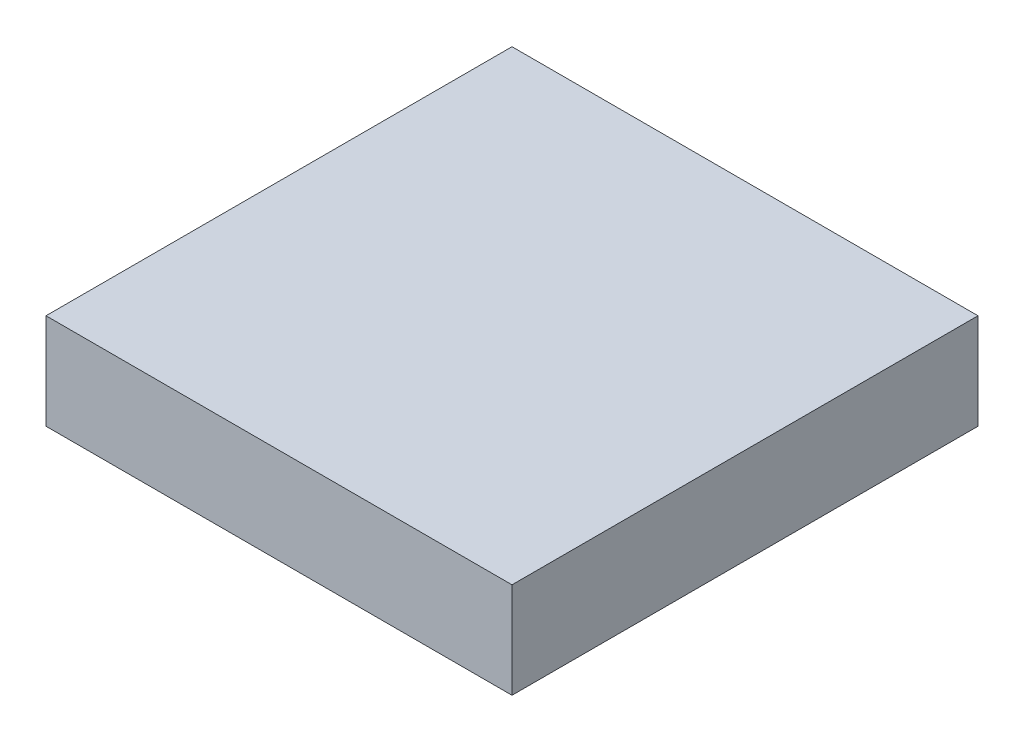
SolidWorks part; units mm, degrees
material "Pine"
ref_plane "Front Plane" through (0, 0, 0) normal (0, 0, 1) x (1, 0, 0)
ref_plane "Top Plane" through (0, 0, 0) normal (0, 1, 0) x (1, 0, 0)
ref_plane "Right Plane" through (0, 0, 0) normal (1, 0, 0) x (0, 0, -1)
sketch "Sketch1" plane through (0, 0, 0) normal (0, 1, 0) x (1, 0, 0)
  line L1 (-44.45, 44.45) -> (44.45, 44.45)
  line L2 (-44.45, 44.45) -> (-44.45, -44.45)
  line L3 (-44.45, -44.45) -> (44.45, -44.45)
  line L4 (44.45, 44.45) -> (44.45, -44.45)
  line L5 (0, -44.45) -> (0, 44.45) construction
  line L6 (-44.45, 0) -> (44.45, 0) construction
  point P0 (0, 0)
  dimension "D1" = 88.9
  dimension "D2" = 88.9
extrude "Boss-Extrude1" add sketch "Sketch1" along normal blind 18.2562
